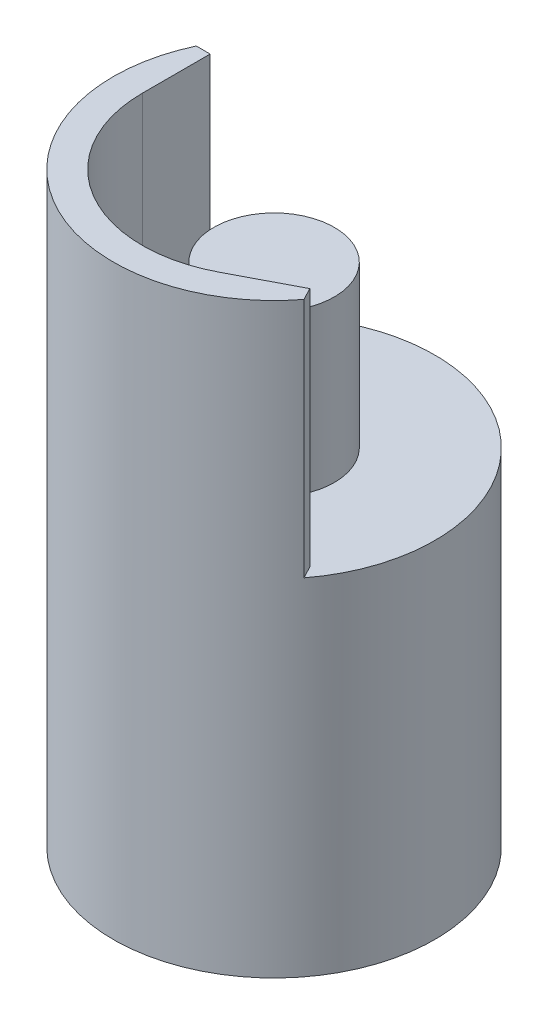
SolidWorks part; units mm, degrees
ref_plane "Front Plane" through (0, 0, 0) normal (0, 0, 1) x (1, 0, 0)
ref_plane "Top Plane" through (0, 0, 0) normal (0, 1, 0) x (1, 0, 0)
ref_plane "Right Plane" through (0, 0, 0) normal (1, 0, 0) x (0, 0, -1)
sketch "Sketch1" plane through (0, 0, 0) normal (0, 1, 0) x (1, 0, 0)
  line L0 (0, 61.4523) -> (0, -77.0318) construction
  line L1 (-83.6674, 0) -> (93.1882, 0) construction
  circle A0 centre (0, 0) radius 10
  circle A1 centre (0, 0) radius 8.0182
  dimension "D1" = 20
extrude "Boss-Extrude1" add sketch "Sketch1" along normal blind 21.5 contours A0 A1 | A1
sketch "Sketch2" plane through (0, 21.5, 0) normal (0, 1, 0) x (1, 0, 0)
  line L0 (-8.2, 0) -> (-10, 0)
  line L1 (0, 0) -> (-23.8252, 0) construction
  line L2 (0, 0) -> (10.1405, -19.0714) construction
  line L3 (4.6947, -8.8295) -> (3.8497, -7.2402)
  line L4 (-8.2, 0) -> (-8.2, 5.7236)
  line L5 (3.8497, -7.2402) -> (17.6091, 0.0759) construction
  line L6 (3.8497, -7.2402) -> (8.8681, -4.6214)
  line L7 (7.5383, -5.3153) -> (7.9381, -6.0816)
  line L8 (-8.2, 4.2236) -> (-9.0643, 4.2236)
  circle A0 centre (0, 0) radius 8.2
  circle A1 centre (0, 0) radius 10 construction
  circle A2 centre (0, 0) radius 10
  dimension "D1" = 118
  dimension "D2" = 1.5
  dimension "D3" = 20
  dimension "D4" = 16.4
  dimension "D5" = 1.5
extrude "Boss-Extrude2" add sketch "Sketch2" along normal blind 15
sketch "Sketch3" plane through (0, 21.5, 0) normal (0, 1, 0) x (1, 0, 0)
  circle A0 centre (0, 0) radius 3.75
  dimension "D1" = 7.5
extrude "Boss-Extrude3" add sketch "Sketch3" along normal blind 10
sketch "Sketch4" plane through (0, 0, 0) normal (0, 1, 0) x (1, 0, 0)
  line L0 (0, 0) -> (-31.6425, 0) construction
  line L1 (0, 0) -> (0, 22.8851) construction
  line L2 (-13, 0) -> (-10, 0)
  line L3 (0, 13) -> (0, 10)
  line L4 (0, 0) -> (-1.2028, 22.9509) construction
  line L5 (0, 0) -> (-29.0164, 1.5207) construction
  line L6 (-0.6804, 12.9822) -> (-0.5234, 9.9863)
  line L7 (-12.5, 0.6551) -> (-9.9863, 0.5234)
  circle A0 centre (0, 0) radius 10
  arc A1 (-13, 0) -> (0, 13) centre (0, 0) cw
  dimension "D1" = 3
  dimension "D2" = 20
  dimension "D3" = 3
  dimension "D4" = 3
extrude "Boss-Extrude4" add sketch "Sketch4" along normal blind 1.5 contours A1 L2 A0 L3
